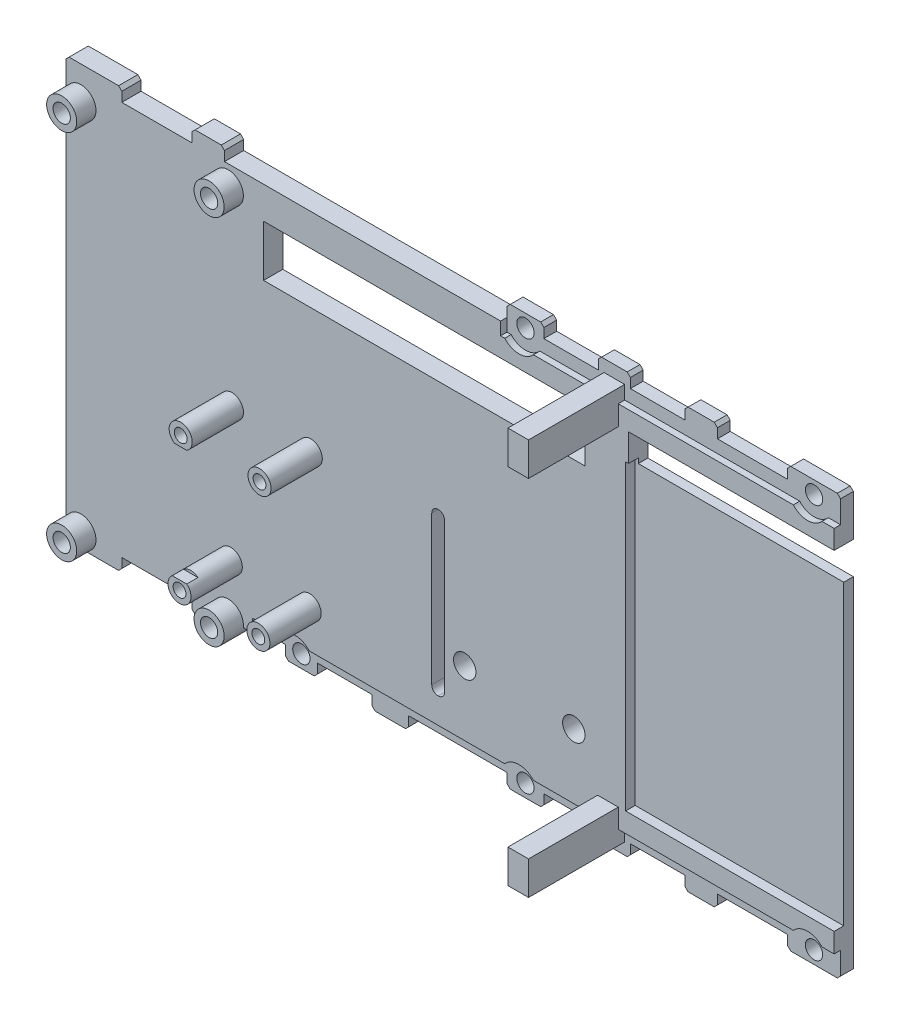
SolidWorks part; units mm, degrees
ref_plane "Front Plane" through (0, 0, 0) normal (0, 0, 1) x (1, 0, 0)
ref_plane "Top Plane" through (0, 0, 0) normal (0, 1, 0) x (1, 0, 0)
ref_plane "Right Plane" through (0, 0, 0) normal (1, 0, 0) x (0, 0, -1)
sketch "Sketch1" plane through (0, 0, 0) normal (0, 0, 1) x (1, 0, 0)
  line L0 (59.7063, -28.75) -> (59.7063, -32.25)
  line L1 (59.7063, -32.25) -> (59.2063, -32.75)
  line L2 (59.2063, -32.75) -> (51.937, -32.75)
  line L3 (51.937, -32.75) -> (51.437, -32.25)
  line L4 (51.437, -32.25) -> (51.437, -30.75)
  line L5 (51.437, -30.75) -> (40.497, -30.75)
  line L6 (40.497, -30.75) -> (40.497, -32.25)
  line L7 (40.497, -32.25) -> (39.997, -32.75)
  line L8 (39.997, -32.75) -> (35.917, -32.75)
  line L9 (35.917, -32.75) -> (35.417, -32.25)
  line L10 (35.417, -32.25) -> (35.417, -30.75)
  line L11 (35.417, -30.75) -> (26.917, -30.75)
  line L12 (26.917, -30.75) -> (26.917, -32.25)
  line L13 (26.917, -32.25) -> (26.417, -32.75)
  line L14 (26.417, -32.75) -> (22.417, -32.75)
  line L15 (22.417, -32.75) -> (21.917, -32.25)
  line L16 (21.917, -32.25) -> (21.917, -30.75)
  line L17 (21.917, -30.75) -> (13.417, -30.75)
  line L18 (13.417, -30.75) -> (13.417, -32.25)
  line L19 (13.417, -32.25) -> (12.917, -32.75)
  line L20 (12.917, -32.75) -> (8.167, -32.75)
  line L21 (8.167, -32.75) -> (7.667, -32.25)
  line L22 (7.667, -32.25) -> (7.667, -30.75)
  line L24 (7.667, 30.75) -> (7.667, 32.25)
  line L25 (7.667, 32.25) -> (8.167, 32.75)
  line L26 (8.167, 32.75) -> (12.917, 32.75)
  line L27 (12.917, 32.75) -> (13.417, 32.25)
  line L28 (13.417, 32.25) -> (13.417, 30.75)
  line L29 (13.417, 30.75) -> (21.917, 30.75)
  line L30 (21.917, 30.75) -> (21.917, 32.25)
  line L31 (21.917, 32.25) -> (22.417, 32.75)
  line L32 (22.417, 32.75) -> (26.417, 32.75)
  line L33 (26.417, 32.75) -> (26.917, 32.25)
  line L34 (26.917, 32.25) -> (26.917, 30.75)
  line L35 (26.917, 30.75) -> (35.417, 30.75)
  line L36 (35.417, 30.75) -> (35.417, 32.25)
  line L37 (35.417, 32.25) -> (35.917, 32.75)
  line L38 (35.917, 32.75) -> (39.997, 32.75)
  line L39 (39.997, 32.75) -> (40.497, 32.25)
  line L40 (40.497, 32.25) -> (40.497, 30.75)
  line L41 (40.497, 30.75) -> (51.437, 30.75)
  line L42 (51.437, 30.75) -> (51.437, 32.25)
  line L43 (51.437, 32.25) -> (51.937, 32.75)
  line L44 (51.937, 32.75) -> (59.2063, 32.75)
  line L45 (59.2063, 32.75) -> (59.7063, 32.25)
  line L46 (59.7063, 32.25) -> (59.7063, 28.75)
  line L47 (59.7063, 28.75) -> (59.7063, -28.75)
  line L48 (10.5458, 30.75) -> (10.542, 32.75) construction
  line L49 (10.5458, 30.75) -> (10.5458, 28.75) construction
  line L50 (-60.167, 28.75) -> (26.083, 28.75) construction
  line L51 (55.5754, 30.75) -> (55.5716, 32.75) construction
  line L52 (55.5754, 30.75) -> (55.5754, 28.75) construction
  line L53 (55.5716, -30.75) -> (55.5716, -28.75) construction
  line L54 (55.5716, -30.75) -> (55.5716, -32.75) construction
  line L55 (57.7063, -28.75) -> (30.583, -28.75) construction
  line L56 (10.542, -30.75) -> (10.542, -28.75) construction
  line L57 (10.542, -30.75) -> (10.542, -32.75) construction
  line L58 (26.083, -28.75) -> (-60.167, -28.75) construction
  line L59 (30.583, 28.75) -> (59.7063, 28.75) construction
  line L60 (7.667, 30.75) -> (-35.417, 30.75)
  line L61 (-35.417, 30.75) -> (-35.417, 32.25)
  line L62 (-35.417, 32.25) -> (-35.917, 32.75)
  line L63 (-35.917, 32.75) -> (-39.997, 32.75)
  line L64 (-39.997, 32.75) -> (-40.497, 32.25)
  line L65 (-40.497, 32.25) -> (-40.497, 30.75)
  line L66 (-40.497, 30.75) -> (-51.437, 30.75)
  line L67 (-51.437, 30.75) -> (-51.437, 32.25)
  line L68 (-51.437, 32.25) -> (-51.937, 32.75)
  line L69 (-51.937, 32.75) -> (-59.6639, 32.75)
  line L70 (-59.6639, 32.75) -> (-60.1639, 32.25)
  line L71 (-60.1639, 32.25) -> (-60.1639, -32.25)
  line L72 (-60.1639, -32.25) -> (-59.6639, -32.75)
  line L73 (-59.6639, -32.75) -> (-51.937, -32.75)
  line L74 (-51.937, -32.75) -> (-51.437, -32.25)
  line L75 (-51.937, -32.75) -> (-51.437, -32.25) construction
  line L76 (-51.437, -32.25) -> (-51.437, -30.75)
  line L77 (-51.437, -30.75) -> (-40.497, -30.75)
  line L78 (-40.497, -30.75) -> (-40.497, -32.25)
  line L79 (-40.497, -32.25) -> (-39.997, -32.75)
  line L80 (-39.997, -32.75) -> (-35.917, -32.75)
  line L81 (-35.917, -32.75) -> (-35.417, -32.25)
  line L82 (-35.417, -32.25) -> (-35.417, -30.75)
  line L83 (-35.417, -30.75) -> (-26.917, -30.75)
  line L84 (-26.917, -30.75) -> (-26.917, -32.25)
  line L85 (-26.917, -32.25) -> (-26.417, -32.75)
  line L86 (-26.417, -32.75) -> (-22.417, -32.75)
  line L87 (-22.417, -32.75) -> (-21.917, -32.25)
  line L88 (-21.917, -32.25) -> (-21.917, -30.75)
  line L89 (-21.917, -30.75) -> (-13.417, -30.75)
  line L90 (-13.417, -30.75) -> (-13.417, -32.25)
  line L91 (-13.417, -32.25) -> (-12.917, -32.75)
  line L92 (-12.917, -32.75) -> (-8.167, -32.75)
  line L93 (-8.167, -32.75) -> (-7.667, -32.25)
  line L94 (-7.667, -32.25) -> (-7.667, -30.75)
  line L95 (-7.667, -30.75) -> (7.667, -30.75)
  circle A0 centre (10.5458, 30.75) radius 1.35
  circle A1 centre (55.5754, 30.75) radius 1.35
  circle A2 centre (55.5716, -30.75) radius 1.35
  circle A3 centre (10.542, -30.75) radius 1.35
  circle A4 centre (-24.417, -30.75) radius 1.35
  point P107 (55.5716, 32.75)
  point P113 (55.5716, -32.75)
  point P128 (10.542, -32.75)
  point P192 (-24.417, -32.75)
  dimension "D1" = 2.7
  dimension "D2" = 2.7
extrude "Boss-Extrude1" add sketch "Sketch1" along normal blind 3
sketch "Sketch2" plane through (0, 0, 3) normal (0, 0, 1) x (1, 0, 0)
  line L0 (59.7063, -32.25) -> (59.7063, 32.25) construction
  line L1 (58.7063, 20.5) -> (28.167, 20.5) construction
  line L2 (58.7063, 20.5) -> (58.7063, -24.7) construction
  line L3 (58.7063, -24.7) -> (28.167, -24.7) construction
  line L4 (28.167, 20.5) -> (28.167, -24.7) construction
  line L8 (71.357, 25.7) -> (-4.643, 25.7) construction
  line L10 (-4.643, 25.7) -> (-4.643, -25.7) construction
  line L12 (59.7063, -25.7) -> (27.167, -25.7)
  line L13 (27.167, 21.5) -> (27.167, -25.7)
  line L14 (59.7063, 21.5) -> (27.167, 21.5)
  line L15 (59.7063, 21.5) -> (59.7063, -25.7)
  line L16 (-4.643, -25.7) -> (71.357, -25.7) construction
  line L17 (71.357, -25.7) -> (71.357, 25.7) construction
  line L18 (17.667, -30.75) -> (17.667, -25.7) construction
  line L19 (13.417, -30.75) -> (21.917, -30.75) construction
  line L20 (17.667, 30.75) -> (17.667, 25.7) construction
  line L21 (21.917, 30.75) -> (13.417, 30.75) construction
  dimension "D1" = 1
  dimension "D2" = 45.2
  dimension "D3" = 30.5393
  dimension "D4" = 76
  dimension "D5" = 51.4
extrude "Cut-Extrude1" cut sketch "Sketch2" against normal blind 1.5
sketch "Sketch3" plane through (0, 0, 3) normal (0, 0, 1) x (1, 0, 0)
  line L1 (7.667, 28.75) -> (8.3097, 28.75)
  line L2 (7.667, 28.75) -> (7.667, 32.75)
  line L3 (7.667, 32.75) -> (59.7063, 32.75)
  line L4 (59.7063, 28.75) -> (59.7063, 32.75)
  line L5 (-60.167, 28.75) -> (26.083, 28.75) construction
  line L6 (12.917, 32.75) -> (8.167, 32.75) construction
  line L7 (59.7063, 21.5) -> (59.7063, 32.25) construction
  line L8 (26.083, -28.75) -> (-60.167, -28.75) construction
  line L9 (-31.0693, -28.75) -> (-26.6531, -28.75)
  line L10 (-31.0693, -28.75) -> (-31.0693, -32.75)
  line L12 (59.7063, -28.75) -> (59.7063, -32.75)
  line L13 (12.7818, 28.75) -> (53.3393, 28.75)
  line L14 (57.8115, 28.75) -> (59.7063, 28.75)
  line L15 (57.8077, -28.75) -> (59.7063, -28.75)
  line L16 (12.7781, -28.75) -> (53.3356, -28.75)
  line L19 (7.667, 32.25) -> (7.667, 30.75) construction
  line L20 (-31.0693, 37) -> (-31.0693, 30.75) construction
  line L21 (59.7063, -32.25) -> (59.7063, -25.7) construction
  line L22 (-26.417, -32.75) -> (-22.417, -32.75) construction
  line L23 (-31.0693, -32.75) -> (-26.6531, -32.75)
  line L24 (-22.1809, -32.75) -> (59.7063, -32.75)
  line L25 (-22.1809, -28.75) -> (8.3059, -28.75)
  arc A0 (12.7781, -28.75) -> (8.3059, -28.75) centre (10.542, -30.75) ccw
  arc A1 (57.8077, -28.75) -> (53.3356, -28.75) centre (55.5716, -30.75) ccw
  arc A3 (53.3393, 28.75) -> (57.8115, 28.75) centre (55.5754, 30.75) ccw
  arc A4 (8.3097, 28.75) -> (12.7818, 28.75) centre (10.5458, 30.75) ccw
  arc A5 (-26.6531, -32.75) -> (-22.1809, -32.75) centre (-24.417, -30.75) ccw
  arc A6 (-22.1809, -28.75) -> (-26.6531, -28.75) centre (-24.417, -30.75) ccw
  point P43 (-24.417, -32.75)
  dimension "D1" = 6
  dimension "D2" = 6
  dimension "D3" = 6
  dimension "D4" = 6
extrude "Cut-Extrude2" cut sketch "Sketch3" against normal blind 1
sketch "Sketch4" plane through (0, 0, 3) normal (0, 0, 1) x (1, 0, 0)
  line L1 (27.647, 25.77) -> (66.827, 25.77)
  line L2 (27.647, 25.77) -> (27.647, 20.73)
  line L3 (27.647, 20.73) -> (66.827, 20.73)
  line L4 (66.827, 25.77) -> (66.827, 20.73)
  line L5 (65.827, 21.73) -> (65.827, 24.77) construction
  line L6 (43.887, 24.77) -> (28.647, 24.77) construction
  line L7 (28.647, 21.73) -> (43.887, 21.73) construction
  line L8 (28.647, 24.77) -> (28.647, 21.73) construction
  dimension "D1" = 1
  dimension "D2" = 1
  dimension "D3" = 1
  dimension "D4" = 1
extrude "Cut-Extrude3" cut sketch "Sketch4" against normal up to surface (3 mm away) up to face at (11.892, -30.75, 0)
sketch "Sketch5" plane through (0, 0, 3) normal (0, 0, 1) x (1, 0, 0)
  line L0 (-5.833, -25.75) -> (70.167, -25.75) construction
  line L1 (22.8101, -30.9676) -> (26.0238, -30.9676)
  line L2 (22.8101, -30.9676) -> (22.8101, -25.75)
  line L3 (22.8101, -25.75) -> (26.0238, -25.75)
  line L4 (26.0238, -30.9676) -> (26.0238, -25.75)
  line L10 (22.417, -32.75) -> (26.417, -32.75) construction
  line L12 (70.167, -0.05) -> (-5.833, -0.05) construction
  line L13 (70.167, -25.75) -> (70.167, 25.65) construction
  line L14 (-5.833, 25.65) -> (-5.833, -25.75) construction
  line L15 (-5.833, -25.75) -> (70.167, -25.75) construction
  line L20 (22.8101, 25.65) -> (26.0238, 25.65)
  line L21 (26.0238, 30.8676) -> (26.0238, 25.65)
  line L22 (22.8101, 30.8676) -> (26.0238, 30.8676)
  line L23 (22.8101, 30.8676) -> (22.8101, 25.65)
  point P14 (24.417, -32.75)
  point P15 (24.417, -30.9676)
extrude "Boss-Extrude3" add sketch "Sketch5" along normal blind 15 from surface at -1 starting at face at (56.9216, -30.75, 2)
sketch "Sketch6" plane through (0, 0, 0) normal (0, 0, -1) x (-1, 0, 0)
  line L1 (59.6639, -32.75) -> (51.937, -32.75) construction
  line L2 (60.1639, 32.25) -> (60.1639, -32.25) construction
  circle A1 centre (34.8148, 27.5978) radius 1.35 construction
  circle A2 centre (57.8139, 27.5978) radius 1.35 construction
  circle A3 centre (57.8139, -30.4) radius 1.35 construction
  circle A4 centre (34.8148, -30.4) radius 1.35 construction
  circle A5 centre (57.8139, -30.4) radius 2.35
  circle A6 centre (34.8148, -30.4) radius 2.35
  circle A7 centre (34.8148, 27.5978) radius 2.35
  circle A8 centre (57.8139, 27.5978) radius 2.35
  dimension "D1" = 2.7
  dimension "D6" = 2.7
  dimension "D2" = 57.9978
  dimension "D3" = 22.9991
  dimension "D4" = 1
extrude "Boss-Extrude4" add sketch "Sketch6" against normal blind 6
sketch "Sketch7" plane through (0, 0, 6) normal (0, 0, 1) x (1, 0, 0)
  circle A0 centre (-57.8139, 27.5978) radius 1.35
  circle A1 centre (-34.8148, 27.5978) radius 1.35
  circle A2 centre (-34.8148, -30.4) radius 1.35
  circle A3 centre (-57.8139, -30.4) radius 1.35
  dimension "D1" = 2.7
  dimension "D2" = 2.7
  dimension "D3" = 2.7
  dimension "D4" = 2.7
extrude "Cut-Extrude4" cut sketch "Sketch7" against normal blind 3
sketch "Sketch8" plane through (0, 0, 3) normal (0, 0, 1) x (1, 0, 0)
  circle A0 centre (-34.249, -1.6711) radius 1.05 construction
  circle A1 centre (-34.249, -1.6711) radius 1.7999
  circle A2 centre (-21.9499, -1.7784) radius 1.05 construction
  circle A3 centre (-21.9499, -1.7784) radius 1.7999
  circle A4 centre (-22.1245, -22.7777) radius 1.05 construction
  circle A5 centre (-22.1245, -22.7777) radius 1.7999
  circle A6 centre (-34.4323, -22.6703) radius 1.05 construction
  circle A7 centre (-34.4323, -22.6703) radius 1.7999
extrude "Boss-Extrude5" add sketch "Sketch8" along normal blind 8
sketch "Sketch9" plane through (0, 0, 11) normal (0, 0, 1) x (1, 0, 0)
  circle A0 centre (-34.4323, -22.6703) radius 1
  circle A1 centre (-22.1332, -22.7776) radius 1
  circle A2 centre (-34.249, -1.6711) radius 1
  circle A3 centre (-21.9499, -1.7784) radius 1
  dimension "D1" = 2
extrude "Cut-Extrude5" cut sketch "Sketch9" against normal up to surface (11 mm away) up to face at (4.5915, -3.4656, 0)
sketch "Sketch10" plane through (0, 0, 3) normal (0, 0, 1) x (1, 0, 0)
  line L0 (-5.833, -25.75) -> (70.167, -25.75) construction
  line L1 (-2.0786, -24.7703) -> (-2.0686, -24.7703)
  line L2 (-3.0786, -23.7703) -> (-3.0786, -0.5703)
  line L3 (-2.0786, 0.4297) -> (-2.0686, 0.4297)
  line L4 (-1.0686, -23.7703) -> (-1.0686, -0.5703)
  line L6 (-36.2323, 0.4297) -> (-12.2323, 0.4297) construction
  line L8 (-36.2323, -24.7703) -> (-12.2323, -24.7703) construction
  arc A0 (-2.0786, -24.7703) -> (-3.0786, -23.7703) centre (-2.0786, -23.7703) cw
  arc A1 (-2.0686, -24.7703) -> (-1.0686, -23.7703) centre (-2.0686, -23.7703) ccw
  arc A2 (-2.0686, 0.4297) -> (-1.0686, -0.5703) centre (-2.0686, -0.5703) cw
  arc A3 (-3.0786, -0.5703) -> (-2.0786, 0.4297) centre (-2.0786, -0.5703) cw
  point P8 (-3.0786, -25.75)
  dimension "D1" = 1
  dimension "D2" = 2.01
extrude "Cut-Extrude6" cut sketch "Sketch10" against normal up to surface (3 mm away) up to face at (-23.1332, -22.7776, 0)
sketch "Sketch11" plane through (0, 0, 3) normal (0, 0, 1) x (1, 0, 0)
  line L0 (-31.3148, 10.7478) -> (-31.3148, 28.1478) construction
  line L1 (-29.3148, 25.75) -> (20.8101, 25.75)
  line L2 (-29.3148, 25.75) -> (-29.3148, 17.75)
  line L3 (-29.3148, 17.75) -> (20.8101, 17.75)
  line L4 (20.8101, 25.75) -> (20.8101, 17.75)
  line L5 (22.8101, 28.75) -> (22.8101, 25.65) construction
  arc A0 (8.3097, 28.75) -> (12.7818, 28.75) centre (10.5458, 30.75) ccw construction
  point P7 (10.5458, 27.75)
  dimension "D1" = 2
  dimension "D2" = 2
  dimension "D3" = 2
  dimension "D4" = 8
extrude "Cut-Extrude7" cut sketch "Sketch11" against normal up to surface (3 mm away) up to face at (-2.0736, -12.1703, 0)
sketch "Sketch12" plane through (0, 0, 11) normal (0, 0, 1) x (1, 0, 0)
  line L0 (-23.2323, -21.2703) -> (-35.2323, -21.2703) construction
  line L1 (-33.301, -21.2703) -> (-35.5635, -21.2703)
  line L2 (-33.301, -21.2703) -> (-33.301, -3.2011)
  line L3 (-33.301, -3.2011) -> (-35.5635, -3.2011)
  line L4 (-35.5635, -21.2703) -> (-35.5635, -3.2011)
  circle A0 centre (-34.4323, -22.6703) radius 1.7999 construction
  circle A1 centre (-34.249, -1.6711) radius 1.7999 construction
extrude "Cut-Extrude8" cut sketch "Sketch12" against normal blind 1.75
sketch "Sketch13" plane through (0, 0, 3) normal (0, 0, 1) x (1, 0, 0)
  line L0 (2.067, -16.75) -> (2.067, -20.55) construction
  circle A0 centre (19.0923, -18.65) radius 1.75
  circle A1 centre (2.067, -18.65) radius 1.75
  point P2 (0, 0)
  point P3 (19.0923, -18.65)
  point P6 (0, 0)
  point P7 (2.067, -18.65)
  dimension "D1" = 3.5
extrude "Cut-Extrude9" cut sketch "Sketch13" against normal up to surface (3 mm away) up to face at (-4.2523, 21.75, 0)
